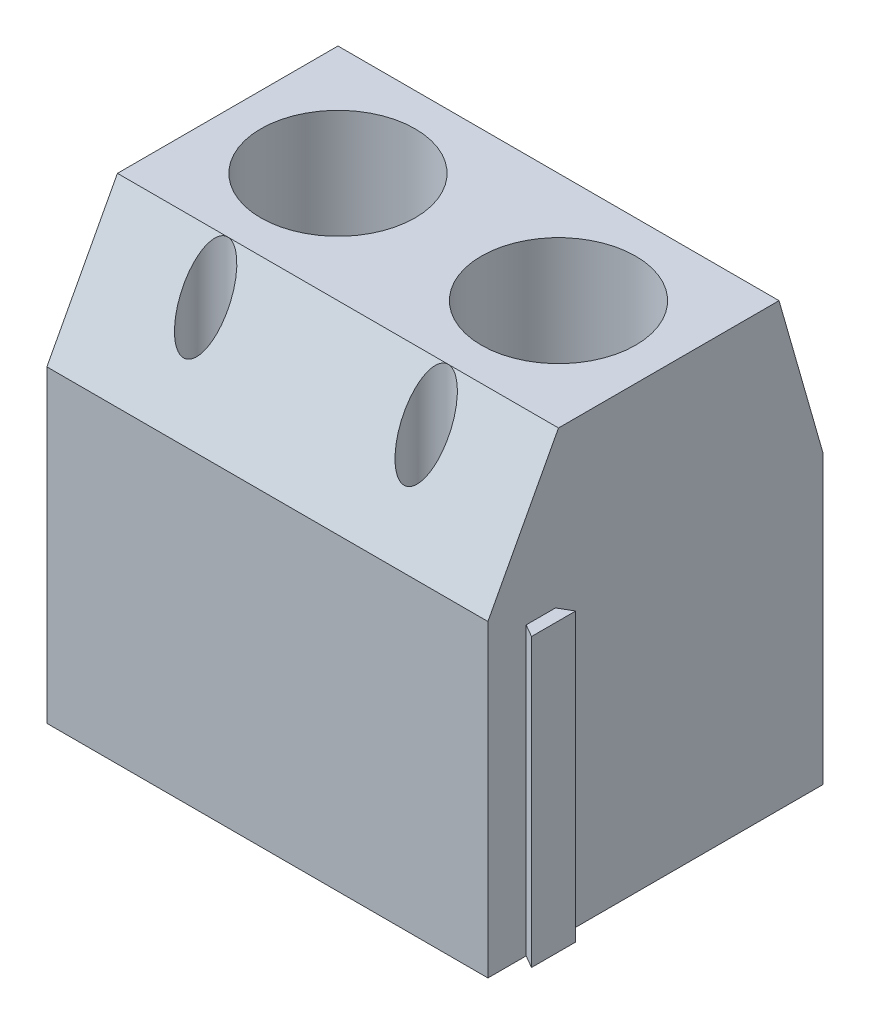
SolidWorks part; units mm, degrees
ref_plane "Front Plane" through (0, 0, 0) normal (0, 0, 1) x (1, 0, 0)
ref_plane "Top Plane" through (0, 0, 0) normal (0, 1, 0) x (1, 0, 0)
ref_plane "Right Plane" through (0, 0, 0) normal (1, 0, 0) x (0, 0, -1)
sketch "Sketch1" plane through (0, 0, 0) normal (0, 1, 0) x (1, 0, 0)
  line L0 (-4.7482, 3.126) -> (-4.7482, 3.9332)
  line L1 (-4.7482, -3.6668) -> (5.2518, -3.6668)
  line L2 (-4.7482, -3.6668) -> (-4.7482, -2.8002)
  line L3 (-4.7482, 3.9332) -> (5.0605, 3.9332)
  line L4 (5.2518, -3.6668) -> (5.2518, -2.8002)
  line L5 (5.0605, 3.9332) -> (5.2518, 3.9332)
  line L6 (-4.7482, 3.126) -> (-4.7482, 1.7404)
  line L7 (5.2518, 2.9928) -> (5.2518, 1.6072)
  line L8 (-4.7482, -2.1335) -> (-4.7482, 1.7404)
  line L9 (-4.7482, -2.8002) -> (-4.4595, -2.9668)
  line L10 (-4.4595, -2.9668) -> (-4.4595, -1.9668)
  line L11 (-4.4595, -1.9668) -> (-4.7482, -2.1335)
  line L12 (5.2518, -2.8002) -> (5.5405, -2.9668)
  line L13 (5.2518, 2.9928) -> (5.2518, 3.9332)
  line L14 (5.5405, -2.9668) -> (5.5405, -1.9668)
  line L15 (5.5405, -1.9668) -> (5.2518, -2.1335)
  line L16 (5.2518, -2.1335) -> (5.2518, 1.6072)
  point P0 (0, 0)
  dimension "D1" = 10
  dimension "D2" = 7.6
  dimension "D3" = 1
  dimension "D5" = 1
extrude "Boss-Extrude1" add sketch "Sketch1" along normal blind 6.5
sketch "Sketch2" plane through (0, 0, -3.9332) normal (0, 0, -1) x (-1, 0, 0)
  line L0 (-5.2518, 6.5) -> (4.7482, 6.5) construction
  line L1 (-4.7518, 0.5) -> (-0.7518, 0.5)
  line L2 (-4.7518, 0.5) -> (-4.7518, 5.5)
  line L3 (-4.7518, 5.5) -> (-0.7518, 5.5)
  line L4 (-0.7518, 0.5) -> (-0.7518, 5.5)
  line L5 (-4.7518, 0.5) -> (-0.7518, 5.5) construction
  line L6 (-4.7518, 5.5) -> (-0.7518, 0.5) construction
  line L7 (-5.2518, 6.5) -> (-5.2518, 0) construction
  line L9 (0.2482, 0.5) -> (4.2482, 0.5)
  line L10 (0.2482, 0.5) -> (0.2482, 5.5)
  line L11 (0.2482, 5.5) -> (4.2482, 5.5)
  line L12 (4.2482, 0.5) -> (4.2482, 5.5)
  line L13 (0.2482, 0.5) -> (4.2482, 5.5) construction
  line L14 (0.2482, 5.5) -> (4.2482, 0.5) construction
  point P0 (-2.7518, 3)
  point P9 (2.2482, 3)
  dimension "D1" = 4
  dimension "D2" = 5
  dimension "D3" = 1
  dimension "D4" = 0.5
  dimension "D5" = 4
  dimension "D6" = 5
  dimension "D7" = 1
  dimension "D8" = 1
extrude "Cut-Extrude1" cut sketch "Sketch2" against normal blind 7
sketch "Sketch3" plane through (0, 0, 0) normal (0, -1, 0) x (-1, 0, 0)
  line L0 (-5.2518, 3.9332) -> (4.7482, 3.9332) construction
  line L1 (-3.25, 3.9332) -> (-2.25, 3.9332)
  line L2 (-3.25, 3.9332) -> (-3.25, -0.5768)
  line L3 (-2.76, -1.0668) -> (-2.74, -1.0668)
  line L4 (-2.25, 3.9332) -> (-2.25, -0.5768)
  line L5 (-3.25, 3.9332) -> (-2.25, -1.0668) construction
  line L6 (-3.25, -1.0668) -> (-2.25, 3.9332) construction
  line L8 (1.75, 3.9332) -> (2.75, 3.9332)
  line L9 (1.75, 3.9332) -> (1.75, -0.5768)
  line L10 (2.24, -1.0668) -> (2.26, -1.0668)
  line L11 (2.75, 3.9332) -> (2.75, -0.5768)
  line L12 (1.75, 3.9332) -> (2.75, -1.0668) construction
  line L13 (1.75, -1.0668) -> (2.75, 3.9332) construction
  arc A0 (-2.74, -1.0668) -> (-2.25, -0.5768) centre (-2.74, -0.5768) ccw
  arc A1 (-3.25, -0.5768) -> (-2.76, -1.0668) centre (-2.76, -0.5768) ccw
  arc A2 (2.26, -1.0668) -> (2.75, -0.5768) centre (2.26, -0.5768) ccw
  arc A3 (1.75, -0.5768) -> (2.24, -1.0668) centre (2.24, -0.5768) ccw
  point P0 (-2.75, 1.4332)
  point P14 (2.25, 1.4332)
  dimension "D5" = 0.49
  dimension "D10" = 0.49
  dimension "D1" = 5
  dimension "D2" = 1
  dimension "D3" = 2.75
  dimension "D4" = 0
  dimension "D6" = 5
  dimension "D7" = 1
  dimension "D8" = 0
  dimension "D9" = 2.25
extrude "Cut-Extrude2" cut sketch "Sketch3" against normal blind 0.5
sketch "Sketch4" plane through (5.2518, 0, 0) normal (1, 0, 0) x (0, 0, -1)
  line L0 (3.9332, 6.5) -> (-3.6668, 6.5)
  line L1 (-3.6668, 6.5) -> (-3.6668, 7)
  line L2 (-3.6668, 7) -> (-2.0668, 10)
  line L3 (-2.0668, 10) -> (2.9332, 10)
  line L4 (2.9332, 10) -> (3.9332, 6.5)
  dimension "D1" = 3.5
  dimension "D2" = 5
  dimension "D3" = 1
  dimension "D4" = 0.5
  dimension "D5" = 3
extrude "Boss-Extrude2" add sketch "Sketch4" against normal blind 10
sketch "Sketch5" plane through (0, 10, 0) normal (0, 1, 0) x (1, 0, 0)
  line L0 (5.2518, 3.9332) -> (-4.7482, 3.9332) construction
  line L1 (-4.7482, 2.9332) -> (-4.7482, -2.0668) construction
  line L2 (5.2518, 2.9332) -> (5.2518, -2.0668) construction
  line L3 (-4.7482, -2.0668) -> (5.2518, -2.0668) construction
  line L4 (-4.7482, -2.0668) -> (-4.7482, -3.6668) construction
  line L5 (5.2518, -2.0668) -> (5.2518, -3.6668) construction
  circle A0 centre (-2.2482, 0.4332) radius 1.75
  circle A1 centre (2.7518, 0.4332) radius 1.75
  circle A2 centre (-2.2482, -2.5668) radius 0.5
  circle A3 centre (2.7518, -2.5668) radius 0.5
  point P20 (0, 0)
  dimension "D1" = 3.5
  dimension "D3" = 3.5
  dimension "D6" = 3.5
  dimension "D7" = 1
  dimension "D8" = 1
  dimension "D2" = 2.5
  dimension "D4" = 3.5
  dimension "D5" = 2.5
  dimension "D9" = 0.5
  dimension "D10" = 0.5
  dimension "D11" = 2.5
  dimension "D12" = 2.5
extrude "Cut-Extrude3" cut sketch "Sketch5" against normal blind 3.5
sketch "Sketch7" plane through (0, 6.5, 0) normal (0, 1, 0) x (1, 0, 0)
  line L0 (5.2518, 3.9332) -> (-4.7482, 3.9332) construction
  line L1 (5.2518, 2.9332) -> (5.2518, -2.0668) construction
  circle A0 centre (-2.25, 0.4332) radius 1
  circle A1 centre (2.7518, 0.4332) radius 1
  dimension "D1" = 3.5
  dimension "D3" = 2
  dimension "D2" = 2.25
  dimension "D4" = 2.5
  dimension "D5" = 3.5
extrude "Cut-Extrude4" cut sketch "Sketch7" against normal blind 1
